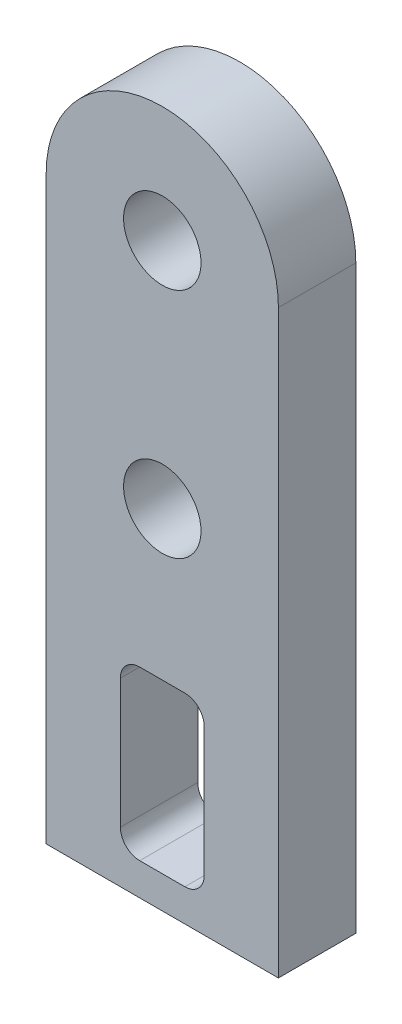
SolidWorks part; units mm, degrees
ref_plane "Alzado" through (0, 0, 0) normal (0, 0, 1) x (1, 0, 0)
ref_plane "Planta" through (0, 0, 0) normal (0, 1, 0) x (1, 0, 0)
ref_plane "Vista lateral" through (0, 0, 0) normal (1, 0, 0) x (0, 0, -1)
sketch "Model" plane through (0, 0, 0) normal (0, 0, 1) x (1, 0, 0)
  line L0 (202.9732, 160.0566) -> (202.9732, 182.5566)
  line L1 (211.9732, 160.0566) -> (202.9732, 160.0566)
  line L2 (211.9732, 182.5566) -> (211.9732, 160.0566)
  line L3 (205.8482, 162.0566) -> (205.8482, 167.0566)
  line L4 (206.5982, 167.8066) -> (208.3482, 167.8066)
  line L5 (209.0982, 167.0566) -> (209.0982, 162.0566)
  line L6 (208.3482, 161.3066) -> (206.5982, 161.3066)
  circle A0 centre (207.4732, 173.5566) radius 1.5
  arc A1 (211.9732, 182.5566) -> (202.9732, 182.5566) centre (207.4732, 182.5566) ccw
  circle A2 centre (207.4732, 182.5566) radius 1.5
  arc A3 (206.5982, 167.8066) -> (205.8482, 167.0566) centre (206.5982, 167.0566) ccw
  arc A4 (209.0982, 167.0566) -> (208.3482, 167.8066) centre (208.3482, 167.0566) ccw
  arc A5 (208.3482, 161.3066) -> (209.0982, 162.0566) centre (208.3482, 162.0566) ccw
  arc A6 (205.8482, 162.0566) -> (206.5982, 161.3066) centre (206.5982, 162.0566) ccw
extrude "Saliente-Extruir1" add sketch "Model" along normal blind 3
